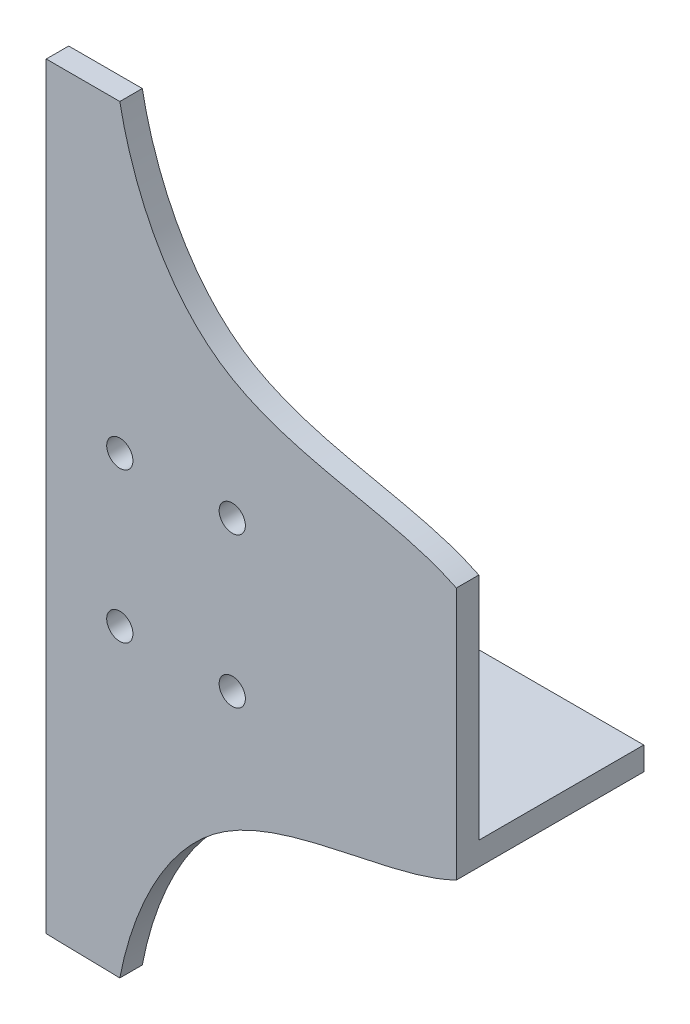
SolidWorks part; units mm, degrees
ref_plane "Front Plane" through (0, 0, 0) normal (0, 0, 1) x (1, 0, 0)
ref_plane "Top Plane" through (0, 0, 0) normal (0, 1, 0) x (1, 0, 0)
ref_plane "Right Plane" through (0, 0, 0) normal (1, 0, 0) x (0, 0, -1)
sketch "Sketch3" plane through (0, 0, 0) normal (0, 0, 1) x (1, 0, 0)
  line L0 (0, 0) -> (17.9222, 0) construction
  line L8 (0.0334, 50.632) -> (0.0334, -50.4246)
  line L9 (0.0334, -50.4246) -> (9.85, -50.632)
  line L10 (54.7461, -16.8732) -> (54.7461, 16.8732)
  line L11 (9.85, 50.632) -> (0.0334, 50.632)
  circle A2 centre (9.85, 10) radius 1.75
  circle A4 centre (24.85, 10) radius 1.75
  circle A6 centre (24.85, -10) radius 1.75
  circle A8 centre (9.85, -10) radius 1.75
  spline S0 degree 3 poles (54.7461, -16.8732) (45.7885, -21.2886) (21.0378, -20.5399) (11.4853, -41.9879) (9.85, -50.632) knots 0 0 0 0 0.549104 1 1 1 1
  spline S1 degree 3 poles (54.7461, 16.8732) (45.7885, 21.2886) (21.0378, 20.5399) (11.4853, 41.9879) (9.85, 50.632) knots 0 0 0 0 0.549104 1 1 1 1
extrude "Boss-Extrude2" add sketch "Sketch3" along normal blind 3
sketch "Sketch4" plane through (0, 0, 0) normal (0, 0, -1) x (-1, 0, 0)
  line L0 (-54.7461, -13.7617) -> (-0.0334, -13.7617)
  line L1 (-54.7461, -16.8732) -> (-0.0334, -16.8732)
  line L4 (-0.0334, 50.632) -> (-9.85, 50.632)
  line L5 (-54.7461, 16.8732) -> (-54.7461, -16.8732)
  line L6 (-9.85, -50.632) -> (-0.0334, -50.4246)
  line L7 (-0.0334, -50.4246) -> (-0.0334, 50.632)
  line L9 (-54.7461, -13.7617) -> (-54.7461, -16.8732)
  line L11 (-0.0334, -16.8732) -> (-0.0334, -13.7617)
  spline S2 degree 3 poles (-165.6969, -937.1459) (-63.2422, 300.0951) (102.9541, -141.1926) (-209.0491, 115.9153) (502.571, -813.3997) knots -2.578005 -2.578005 -2.578005 -2.578005 0.450896 3.031275 3.031275 3.031275 3.031275 only from (-9.85, 50.632) to (-54.7461, 16.8732)
  spline S4 degree 3 poles (502.5814, 813.4134) (-209.0505, -115.9164) (102.9545, 141.1936) (-63.2422, -300.0951) (-165.6969, 937.146) knots -2.031288 -2.031288 -2.031288 -2.031288 0.549104 3.578006 3.578006 3.578006 3.578006 only from (-54.7461, -16.8732) to (-9.85, -50.632)
  dimension "D1" = 0
extrude "Boss-Extrude3" add sketch "Sketch4" along normal blind 22
sketch "Sketch5" plane through (-1.0646, -50.4014, 0) normal (-0.0211, -0.9998, 0) x (0.9998, -0.0211, 0)
  line L0 (1.0982, -16) -> (55.811, -16)
  line L4 (1.0982, 3) -> (1.0982, 0)
  line L5 (1.0982, 0) -> (10.9171, 0)
  line L6 (1.0982, 0) -> (10.9171, 0)
  line L7 (10.9171, 3) -> (1.0982, 3)
  line L8 (1.0982, -16) -> (1.0982, 0)
  line L13 (10.9171, 0) -> (10.9171, 3)
  line L14 (10.9171, 0) -> (10.9171, 3)
  dimension "D1" = 0
